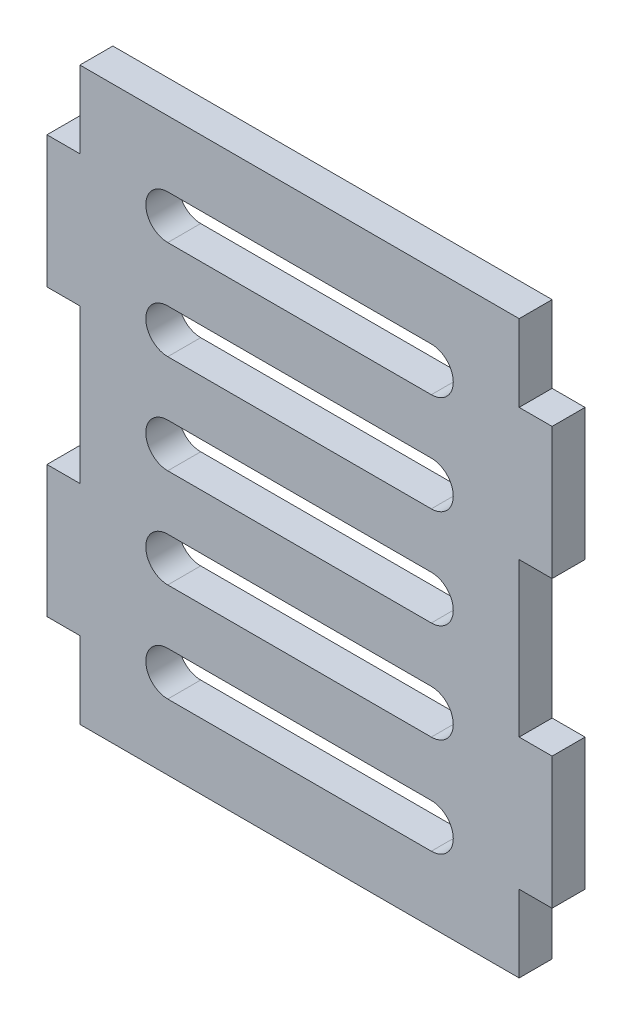
SolidWorks part; units mm, degrees
ref_plane "Front Plane" through (0, 0, 0) normal (0, 0, 1) x (1, 0, 0)
ref_plane "Top Plane" through (0, 0, 0) normal (0, 1, 0) x (1, 0, 0)
ref_plane "Right Plane" through (0, 0, 0) normal (1, 0, 0) x (0, 0, -1)
sketch "Sketch1" plane through (0, 0, 0) normal (0, 0, 1) x (1, 0, 0)
  line L1 (0, 14.4972) -> (20, 14.4972)
  line L2 (0, 14.4972) -> (0, 40.4972)
  line L3 (0, 40.4972) -> (20, 40.4972)
  line L4 (20, 14.4972) -> (20, 40.4972)
  line L5 (0, 14.4972) -> (20, 40.4972) construction
  line L6 (0, 40.4972) -> (20, 14.4972) construction
  line L7 (0, 30.7972) -> (0, 24.1972) construction
  line L10 (20, 30.7972) -> (20, 24.1972) construction
  line L11 (0, 27.4972) -> (20, 27.4972) construction
  line L12 (0, 24.1972) -> (-1.5, 24.1972) construction
  point P4 (10, 27.4972)
  dimension "D1" = 3.3
  dimension "D2" = 26
extrude "Base" add sketch "Sketch1" along normal blind 1.5
sketch "Sketch3" plane through (0, 0, 1.5) normal (0, 0, 1) x (1, 0, 0)
  line L0 (0, 40.4972) -> (0, 14.4972) construction
  line L1 (0, 36.9972) -> (-1.5, 36.9972)
  line L2 (0, 36.9972) -> (0, 30.9972)
  line L3 (0, 30.9972) -> (-1.5, 30.9972)
  line L4 (-1.5, 36.9972) -> (-1.5, 30.9972)
  line L5 (0, 36.9972) -> (-1.5, 30.9972) construction
  line L6 (0, 30.9972) -> (-1.5, 36.9972) construction
  line L8 (10, 33.9972) -> (10, 27.4972) construction
  line L9 (20, 40.4972) -> (0, 40.4972) construction
  line L10 (-1.5, 37.1972) -> (-1.5, 30.7972) construction
  line L11 (0, 27.4972) -> (20, 27.4972) construction
  line L12 (20, 14.4972) -> (20, 40.4972) construction
  line L13 (10, 33.9972) -> (0, 33.9972) construction
  line L14 (10, 33.9972) -> (10, 40.4972) construction
  line L15 (21.5, 36.9972) -> (21.5, 30.9972)
  line L16 (20, 30.9972) -> (21.5, 30.9972)
  line L17 (20, 36.9972) -> (20, 30.9972)
  line L18 (20, 36.9972) -> (21.5, 36.9972)
  line L19 (20, 23.9972) -> (21.5, 23.9972)
  line L20 (21.5, 17.9972) -> (21.5, 23.9972)
  line L21 (20, 17.9972) -> (20, 23.9972)
  line L22 (20, 17.9972) -> (21.5, 17.9972)
  line L23 (-1.5, 17.9972) -> (-1.5, 23.9972)
  line L24 (0, 23.9972) -> (-1.5, 23.9972)
  line L25 (0, 17.9972) -> (0, 23.9972)
  line L26 (0, 17.9972) -> (-1.5, 17.9972)
  point P4 (-0.75, 33.9972)
  dimension "D1" = 6
extrude "Mount ears" add sketch "Sketch3" against normal up to surface (1.5 mm away) up to face at (10, 27.4972, 0)
sketch "Sketch5" plane through (0, 0, 1.5) normal (0, 0, 1) x (1, 0, 0)
  line L0 (10, 40.4972) -> (10, 14.4972) construction
  line L1 (20, 40.4972) -> (0, 40.4972) construction
  line L2 (0, 14.4972) -> (20, 14.4972) construction
  line L3 (4, 36.4972) -> (16, 36.4972) construction
  line L4 (4, 37.4972) -> (16, 37.4972)
  line L5 (4, 35.4972) -> (16, 35.4972)
  line L6 (4, 31.9972) -> (16, 31.9972) construction
  line L7 (4, 32.9972) -> (16, 32.9972)
  line L8 (4, 30.9972) -> (16, 30.9972)
  line L9 (4, 27.4972) -> (16, 27.4972) construction
  line L10 (4, 28.4972) -> (16, 28.4972)
  line L11 (4, 26.4972) -> (16, 26.4972)
  line L12 (4, 22.9972) -> (16, 22.9972) construction
  line L13 (4, 23.9972) -> (16, 23.9972)
  line L14 (4, 21.9972) -> (16, 21.9972)
  line L15 (4, 18.4972) -> (16, 18.4972) construction
  line L16 (4, 19.4972) -> (16, 19.4972)
  line L17 (4, 17.4972) -> (16, 17.4972)
  line L18 (0, 27.4972) -> (20, 27.4972) construction
  line L19 (0, 30.9972) -> (0, 23.9972) construction
  line L20 (20, 23.9972) -> (20, 30.9972) construction
  arc A0 (4, 37.4972) -> (4, 35.4972) centre (4, 36.4972) ccw
  arc A1 (16, 35.4972) -> (16, 37.4972) centre (16, 36.4972) ccw
  arc A2 (4, 32.9972) -> (4, 30.9972) centre (4, 31.9972) ccw
  arc A3 (16, 30.9972) -> (16, 32.9972) centre (16, 31.9972) ccw
  arc A4 (4, 28.4972) -> (4, 26.4972) centre (4, 27.4972) ccw
  arc A5 (16, 26.4972) -> (16, 28.4972) centre (16, 27.4972) ccw
  arc A6 (4, 23.9972) -> (4, 21.9972) centre (4, 22.9972) ccw
  arc A7 (16, 21.9972) -> (16, 23.9972) centre (16, 22.9972) ccw
  arc A8 (4, 19.4972) -> (4, 17.4972) centre (4, 18.4972) ccw
  arc A9 (16, 17.4972) -> (16, 19.4972) centre (16, 18.4972) ccw
  point P8 (10, 36.4972)
  point P16 (10, 31.9972)
  point P23 (10, 27.4972)
  point P30 (10, 22.9972)
  point P37 (10, 18.4972)
  point P48 (10, 27.4972)
  dimension "D2" = 12
  dimension "D3" = 2
  dimension "D4" = 4
  dimension "D1" = 5
extrude "Ribs" cut sketch "Sketch5" against normal up to next
